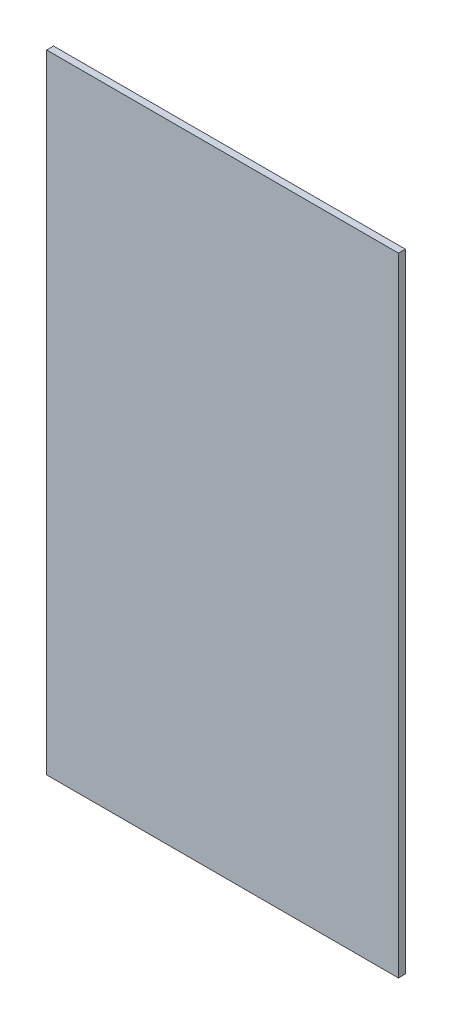
SolidWorks part; units mm, degrees
ref_plane "Front Plane" through (0, 0, 0) normal (0, 0, 1) x (1, 0, 0)
ref_plane "Top Plane" through (0, 0, 0) normal (0, 1, 0) x (1, 0, 0)
ref_plane "Right Plane" through (0, 0, 0) normal (1, 0, 0) x (0, 0, -1)
sketch "Sketch1" plane through (0, 0, 0) normal (0, 0, 1) x (1, 0, 0)
  line L13 (277.5, 22.5) -> (277.5, 477.5)
  line L14 (22.5, 22.5) -> (277.5, 22.5)
  line L15 (22.5, 477.5) -> (22.5, 22.5)
  line L16 (277.5, 477.5) -> (22.5, 477.5)
  line L17 (277.5, 22.5) -> (277.5, 477.5)
  line L18 (22.5, 22.5) -> (277.5, 22.5)
  line L19 (22.5, 477.5) -> (22.5, 22.5)
  line L20 (277.5, 477.5) -> (22.5, 477.5)
  dimension "D1" = 2.5
extrude "Boss-Extrude1" add sketch "Sketch1" against normal blind 5
